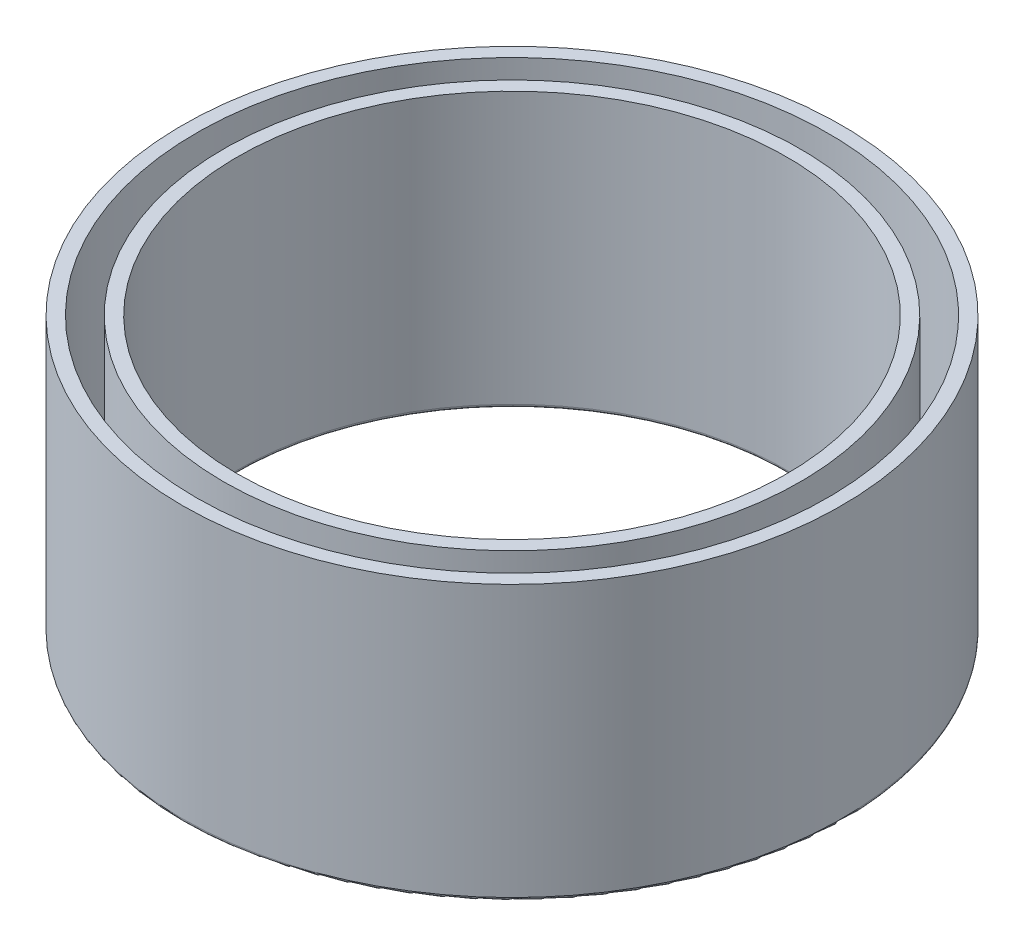
SolidWorks part; units mm, degrees
ref_plane "Front Plane" through (0, 0, 0) normal (0, 0, 1) x (1, 0, 0)
ref_plane "Top Plane" through (0, 0, 0) normal (0, 1, 0) x (1, 0, 0)
ref_plane "Right Plane" through (0, 0, 0) normal (1, 0, 0) x (0, 0, -1)
sketch "Sketch1" plane through (0, 0, 0) normal (0, 1, 0) x (1, 0, 0)
  circle A0 centre (0, 0) radius 20
  circle A1 centre (0, 0) radius 24
  dimension "D1" = 40
  dimension "D2" = 48
extrude "Boss-Extrude1" add sketch "Sketch1" against normal blind 20
shell "Shell4" thickness 1
fillet "Fillet1" radius 0.25 1 edges at (0, -20, 20)
fillet "Fillet2" radius 0.25 1 edges at (0, -20, 24)
